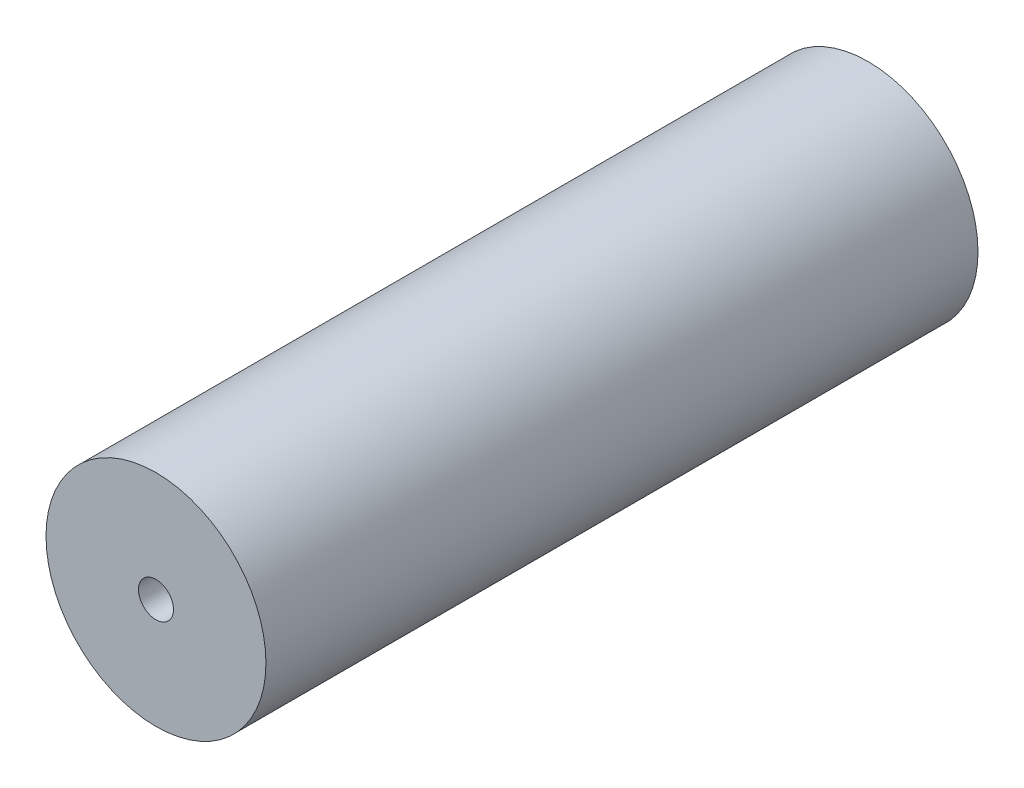
SolidWorks part; units mm, degrees
ref_plane "Front Plane" through (0, 0, 0) normal (0, 0, 1) x (1, 0, 0)
ref_plane "Top Plane" through (0, 0, 0) normal (0, 1, 0) x (1, 0, 0)
ref_plane "Right Plane" through (0, 0, 0) normal (1, 0, 0) x (0, 0, -1)
sketch "Sketch1" plane through (0, 0, 0) normal (0, 0, 1) x (1, 0, 0)
  circle A0 centre (0, 0) radius 12.7
  circle A1 centre (0, 0) radius 2.0193
  dimension "D1" = 25.4
  dimension "D2" = 4.0386
extrude "Boss-Extrude1" add sketch "Sketch1" along normal blind 82.2325
hole_wizard "#10-32 Tapped Hole1" positions "3DSketch1" profile "Sketch5" tap size "#10-32" standard "ANSI Inch" end condition through all
sketch3d "3DSketch1"
  line L0 (0, 0, 82.2325) -> (0, 0, 0) construction
  point P0 (0, 0, 82.2325)
  point P3 (0, 0, 82.2325)
sketch "Sketch5" plane through (0, 0, 82.2325) normal (1, 0, 0) x (0, -1, 0)
  line L0 (0, 0) -> (0, 82.2325)
  line L1 (0, 82.2325) -> (2.0193, 82.2325)
  line L2 (2.0193, 82.2325) -> (2.0193, 0)
  line L5 (2.0193, 0) -> (0, 0)
  line L11 (0, -6.35) -> (0, 107.95) construction
  dimension "Thru Tap Drill Dia." = 4.0386
  dimension "Thru Tap Drill Depth" = 82.2325
cosmetic thread "Hole Thread1" parameters "D2"=4.826
hole_wizard "#10-32 Tapped Hole2" positions "3DSketch2" profile "Sketch6" tap size "#10-32" standard "ANSI Inch" end condition through all
sketch3d "3DSketch2"
  point P0 (0, 0, 0)
  point P3 (0, 0, 0)
  point P5 (0, 0, 0)
sketch "Sketch6" plane through (0, 0, 0) normal (1, 0, 0) x (0, 1, 0)
  line L0 (0, 0) -> (0, 82.2325)
  line L1 (0, 82.2325) -> (2.0193, 82.2325)
  line L2 (2.0193, 82.2325) -> (2.0193, 0)
  line L5 (2.0193, 0) -> (0, 0)
  line L11 (0, -6.35) -> (0, 107.95) construction
  dimension "Thru Tap Drill Dia." = 4.0386
  dimension "Thru Tap Drill Depth" = 82.2325
cosmetic thread "Hole Thread2" parameters "D2"=4.826
